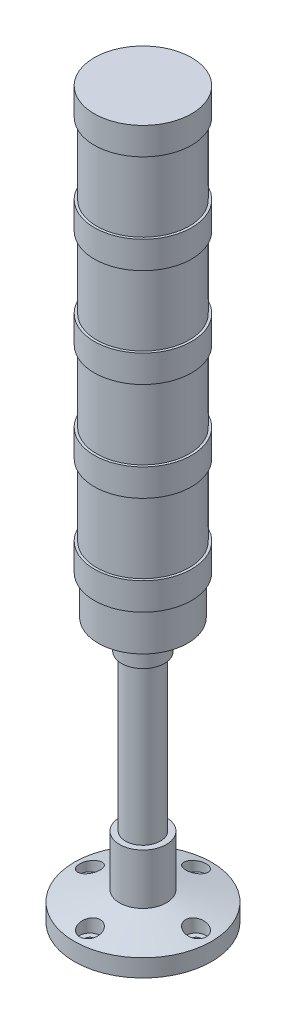
SolidWorks part; units mm, degrees
ref_plane "Płaszczyzna przednia" through (0, 0, 0) normal (0, 0, 1) x (1, 0, 0)
ref_plane "Płaszczyzna górna" through (0, 0, 0) normal (0, 1, 0) x (1, 0, 0)
ref_plane "Płaszczyzna prawa" through (0, 0, 0) normal (1, 0, 0) x (0, 0, -1)
sketch "Sketch1" plane through (0, 0, 0) normal (0, 1, 0) x (1, 0, 0)
  circle A0 centre (0, 0) radius 35.25
  dimension "D1" = 70.5
extrude "Boss-Extrude1" add sketch "Sketch1" along normal blind 9
sketch "Sketch2" plane through (0, 0, 0) normal (0, 0, 1) x (1, 0, 0)
  line L0 (0, 9) -> (0, 14.5)
  line L1 (0, 14.5) -> (12, 14.5)
  line L2 (12, 14.5) -> (35.25, 9)
  line L3 (35.25, 9) -> (0, 9)
  line L4 (35.25, 9) -> (-35.25, 9) construction
  dimension "D2" = 12
revolve "Revolve1" add sketch "Sketch2" angle 360 about L0
sketch "Sketch3" plane through (0, 14.5, 0) normal (0, 1, 0) x (1, 0, 0)
  circle A1 centre (0, 0) radius 12
  circle A2 centre (0, 0) radius 12
  dimension "D1" = 0
extrude "Boss-Extrude2" add sketch "Sketch3" along normal blind 26
sketch "Sketch4" plane through (0, 40.5, 0) normal (0, 1, 0) x (1, 0, 0)
  circle A0 centre (0, 0) radius 9
  dimension "D1" = 18
extrude "Boss-Extrude3" add sketch "Sketch4" along normal blind 80
sketch "Sketch5" plane through (0, 120.5, 0) normal (0, 1, 0) x (1, 0, 0)
  circle A0 centre (0, 0) radius 11
  dimension "D1" = 22
extrude "Boss-Extrude4" add sketch "Sketch5" along normal blind 10
sketch "Sketch6" plane through (0, 0, 0) normal (0, 0, 1) x (1, 0, 0)
  line L0 (0, 130.5) -> (0, 135.5)
  line L1 (11, 130.5) -> (-11, 130.5) construction
  line L2 (0, 135.5) -> (23, 135.5)
  line L3 (23, 135.5) -> (11, 130.5)
  line L4 (11, 130.5) -> (0, 130.5)
  dimension "D1" = 23
  dimension "D2" = 5
revolve "Revolve2" add sketch "Sketch6" angle 360 about L0
sketch "Sketch7" plane through (0, 135.5, 0) normal (0, 1, 0) x (1, 0, 0)
  circle A1 centre (0, 0) radius 23
  circle A2 centre (0, 0) radius 23
  dimension "D1" = 0
extrude "Boss-Extrude5" add sketch "Sketch7" along normal blind 20
sketch "Sketch8" plane through (0, 0, 0) normal (0, 0, 1) x (1, 0, 0)
  line L0 (0, 155.5) -> (25, 155.5)
  line L1 (23, 155.5) -> (-23, 155.5) construction
  line L2 (25, 155.5) -> (25, 169.5)
  line L3 (25, 169.5) -> (23.75, 169.5)
  line L4 (-25, 169.5) -> (-25, 155.5)
  line L5 (-25, 155.5) -> (0, 155.5)
  line L6 (0, 155.5) -> (0, 211.5328) construction
  line L8 (23.75, 169.5) -> (23.75, 206.1402)
  line L10 (-23.75, 206.1402) -> (-23.75, 169.5)
  line L12 (-25, 206.1402) -> (-23.75, 206.1402)
  line L13 (23.75, 206.1402) -> (25, 206.1402)
  line L14 (25, 206.1402) -> (25, 220.1402)
  line L15 (25, 220.1402) -> (23.75, 220.1402)
  line L16 (-25, 220.1402) -> (-25, 206.1402)
  line L19 (23.75, 220.1402) -> (23.75, 256.7803)
  line L21 (-23.75, 256.7803) -> (-23.75, 220.1402)
  line L22 (-25, 256.7803) -> (-23.75, 256.7803)
  line L23 (23.75, 256.7803) -> (25, 256.7803)
  line L24 (25, 256.7803) -> (25, 270.7803)
  line L25 (25, 270.7803) -> (23.75, 270.7803)
  line L26 (-25, 270.7803) -> (-25, 256.7803)
  line L29 (23.75, 270.7803) -> (23.75, 307.4205)
  line L31 (-23.75, 307.4205) -> (-23.75, 270.7803)
  line L32 (-25, 307.4205) -> (-23.75, 307.4205)
  line L33 (23.75, 307.4205) -> (25, 307.4205)
  line L34 (25, 307.4205) -> (25, 321.4205)
  line L35 (25, 321.4205) -> (23.75, 321.4205)
  line L36 (-25, 321.4205) -> (-25, 307.4205)
  line L39 (23.75, 321.4205) -> (23.75, 358.0607)
  line L41 (-23.75, 358.0607) -> (-23.75, 321.4205)
  line L42 (-25, 358.0607) -> (-23.75, 358.0607)
  line L43 (23.75, 358.0607) -> (25, 358.0607)
  line L44 (25, 358.0607) -> (25, 372.0607)
  line L45 (25, 372.0607) -> (-25, 372.0607)
  line L46 (-25, 372.0607) -> (-25, 358.0607)
  line L47 (-23.75, 169.5) -> (-25, 169.5)
  line L48 (0, 155.5) -> (0, 372.0607)
  line L49 (-23.75, 321.4205) -> (-25, 321.4205)
  line L51 (-23.75, 270.7803) -> (-25, 270.7803)
  line L53 (-23.75, 220.1402) -> (-25, 220.1402)
  dimension "D1" = 25
  dimension "D2" = 14
  dimension "D3" = 47.5
  dimension "D4" = 4
  dimension "D5" = 2
revolve "Revolve6" add sketch "Sketch8" angle 360 about L6
sketch "Sketch9" plane through (0, 0, 0) normal (0, -1, 0) x (1, 0, 0)
  circle A0 centre (0, 27.25) radius 2.65
  circle A1 centre (27.25, 0) radius 2.65
  circle A2 centre (0, -27.25) radius 2.65
  circle A3 centre (-27.25, 0) radius 2.65
  point P12 (0, 0)
  dimension "D1" = 27.25
  dimension "D2" = 4
  dimension "D3" = 5.3
extrude "Cut-Extrude1" cut sketch "Sketch9" against normal blind 20
sketch "Sketch11" plane through (0, 0, 0) normal (0, 1, 0) x (1, 0, 0)
  circle A0 centre (0, 27.25) radius 5.25
  circle A1 centre (0, 27.25) radius 2.65 construction
  circle A2 centre (27.25, 0) radius 5.25
  circle A3 centre (0, -27.25) radius 5.25
  circle A4 centre (-27.25, 0) radius 5.25
  point P12 (0, 0)
  dimension "D1" = 10.5
  dimension "D2" = 4
extrude "Cut-Extrude2" cut sketch "Sketch11" against normal blind 40 from offset 45
